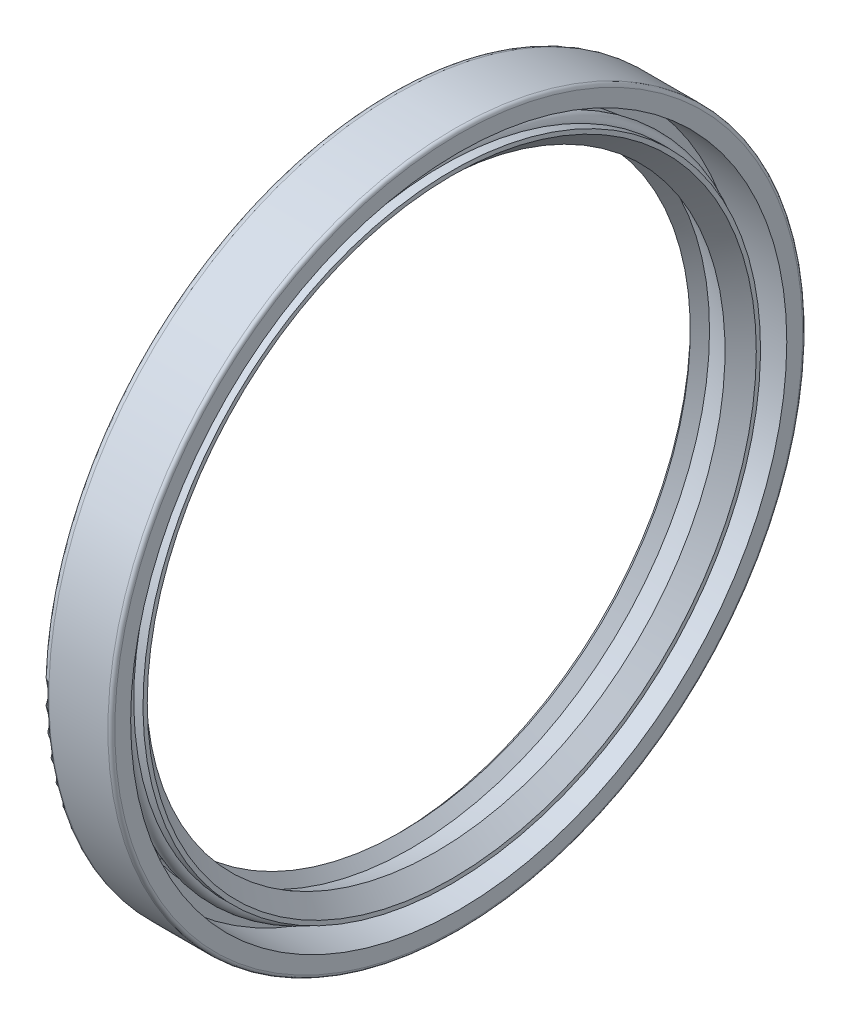
SolidWorks part; units mm, degrees
ref_plane "Front" through (0, 0, 0) normal (0, 0, 1) x (1, 0, 0)
ref_plane "Top" through (0, 0, 0) normal (0, 1, 0) x (1, 0, 0)
ref_plane "Right" through (0, 0, 0) normal (1, 0, 0) x (0, 0, -1)
sketch "Sketch1" plane through (0, 0, 0) normal (0, 0, 1) x (1, 0, 0)
  line L0 (0, 56.6667) -> (0.375, 56.6667)
  line L1 (0.375, 56.6667) -> (0.375, 53.3333)
  line L2 (0.375, 53.3333) -> (0, 53.3333)
  line L3 (0, 53.3333) -> (0, 52.5)
  line L4 (0, 52.5) -> (2, 51.6667)
  line L5 (2, 51.6667) -> (1.1667, 50.8286)
  line L6 (1.1667, 50.8286) -> (2, 50)
  line L7 (2, 50) -> (3.6572, 51.6667)
  line L8 (3.6572, 51.6667) -> (8, 50)
  line L9 (8, 50) -> (10.8, 52.6)
  line L10 (10.8, 52.6) -> (10.8, 53.3333)
  line L11 (10.8, 53.3333) -> (9.2, 53.3333)
  line L12 (6.8, 53.3333) -> (4.6, 53.3333)
  line L13 (4, 53.9333) -> (4, 56.6667)
  line L14 (4, 56.6667) -> (12, 56.6667)
  line L15 (12, 56.6667) -> (12, 59.4)
  line L16 (11.4, 60) -> (1.2, 60)
  line L17 (0, 58.8) -> (0, 56.6667)
  line L18 (12, 0) -> (0, 0) construction
  line L19 (2, 50) -> (8, 50) construction
  line L20 (6.3, 60) -> (6.3, 56.6667) construction
  line L21 (6.3, 56.6667) -> (6.3, 53.3333) construction
  line L22 (6.3, 53.3333) -> (6.3, 50) construction
  line L23 (8, 53.3333) -> (8, 50) construction
  line L24 (0, 57.7333) -> (4, 57.7333) construction
  line L25 (4, 57.7333) -> (8, 57.7333) construction
  line L26 (8, 57.7333) -> (12, 57.7333) construction
  line L27 (8, 53.3333) -> (8, 57.7333) construction
  line L28 (4, 53.9333) -> (3.6572, 51.6667) construction
  line L29 (6.3, 51.6667) -> (3.6572, 51.6667) construction
  line L30 (4.9786, 51.6667) -> (4.9786, 53.3333) construction
  line L31 (4.9786, 52.5) -> (0, 52.5) construction
  line L32 (3.6572, 51.6667) -> (2, 51.6667) construction
  line L33 (2, 50) -> (2, 51.6667) construction
  line L35 (12, 56.6667) -> (12, 53.3333) construction
  line L36 (12, 53.3333) -> (10.8, 53.3333) construction
  line L37 (0, 58.8) -> (1.2, 58.8) construction
  line L39 (2, 57.7333) -> (2, 51.6667) construction
  arc A0 (9.2, 53.3333) -> (6.8, 53.3333) centre (8, 53.3333) ccw construction
  arc A1 (4.6, 53.3333) -> (4, 53.9333) centre (4.6, 53.9333) cw
  arc A2 (12, 59.4) -> (11.4, 60) centre (11.4, 59.4) ccw
  arc A3 (1.2, 60) -> (0, 58.8) centre (1.2, 58.8) ccw
  arc A4 (6.8, 53.3333) -> (9.2, 53.3333) centre (8, 53.3333) ccw
  dimension "D3" = 1.2
  dimension "D4" = 0.6
  dimension "D2" = 0.375
  dimension "D5" = 67.784
  dimension "D8" = 47.121
revolve "Revolve1" add sketch "Sketch1" angle 360 about L18
sketch "Sketch2" plane through (0, 0, 0) normal (0, 0, 1) x (1, 0, 0)
  line L0 (0, 0) -> (12, 0) construction
  circle A0 centre (8, 53.3333) radius 1.2
revolve "Revolve2" add sketch "Sketch2" angle 360 about L0
equation "\"D2@Sketch1\"=\"SealWidth@Sketch1\"*.03125"
equation "\"D3@Sketch1\"=\"SealWidth@Sketch1\"*.1"
equation "\"D4@Sketch1\"=\"D3@Sketch1\"*.5"
